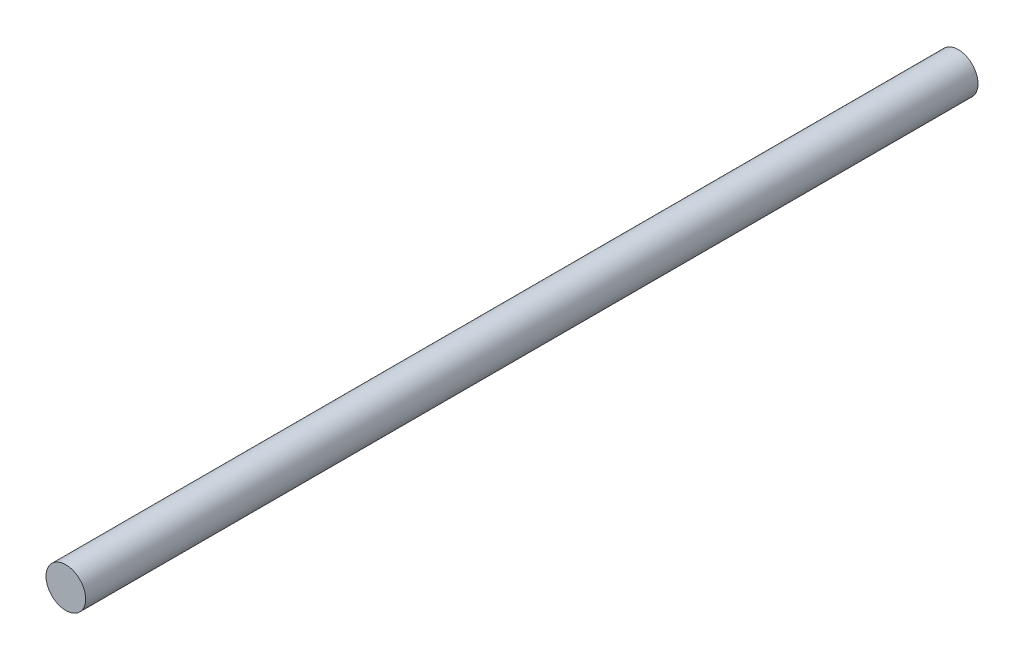
SolidWorks part; units mm, degrees
ref_plane "Alzado" through (0, 0, 0) normal (0, 0, 1) x (1, 0, 0)
ref_plane "Planta" through (0, 0, 0) normal (0, 1, 0) x (1, 0, 0)
ref_plane "Vista lateral" through (0, 0, 0) normal (1, 0, 0) x (0, 0, -1)
sketch "Croquis1" plane through (0, 0, 0) normal (0, 0, 1) x (1, 0, 0)
  circle A0 centre (0, 0) radius 4
  dimension "D1" = 8
extrude "Saliente-Extruir1" add sketch "Croquis1" along normal blind 180
